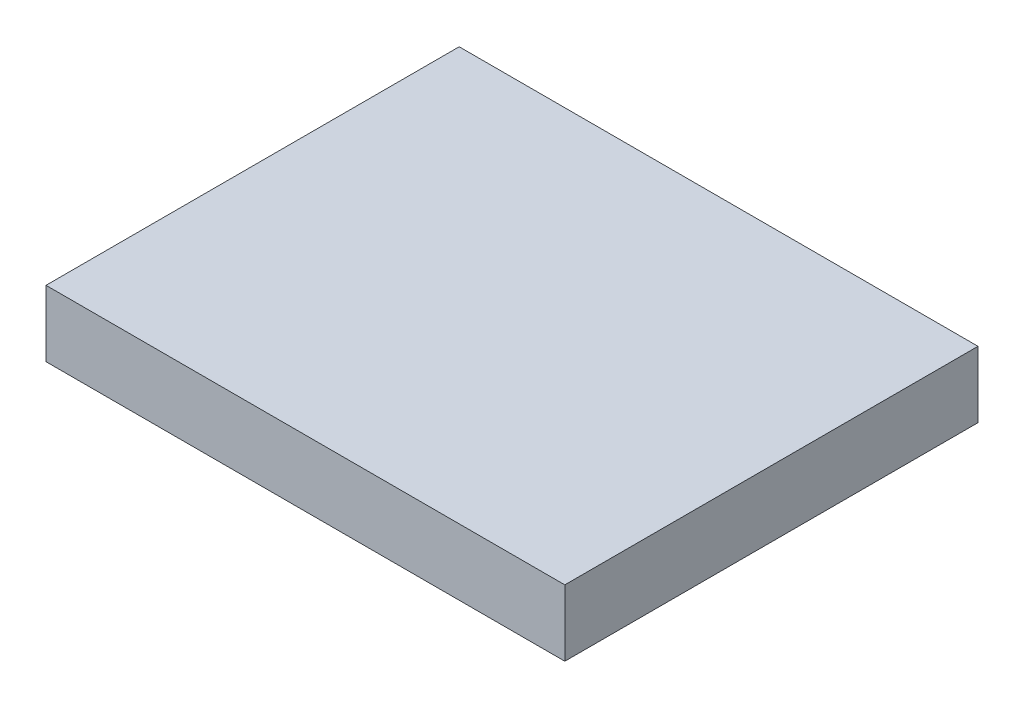
SolidWorks part; units mm, degrees
ref_plane "Front" through (0, 0, 0) normal (0, 0, 1) x (1, 0, 0)
ref_plane "Top" through (0, 0, 0) normal (0, 1, 0) x (1, 0, 0)
ref_plane "Right" through (0, 0, 0) normal (1, 0, 0) x (0, 0, -1)
sketch "Sketch1" plane through (0, 0, 0) normal (0, 1, 0) x (1, 0, 0)
  line L1 (0, 0) -> (424.18, 0)
  line L2 (0, 0) -> (0, 337.82)
  line L3 (0, 337.82) -> (424.18, 337.82)
  line L4 (424.18, 0) -> (424.18, 337.82)
  line L5 (0, 0) -> (424.18, 337.82) construction
  line L6 (0, 337.82) -> (424.18, 0) construction
  point P4 (212.09, 168.91)
  dimension "D1" = 337.82
  dimension "D2" = 424.18
extrude "Boss-Extrude1" add sketch "Sketch1" along normal blind 54.102
